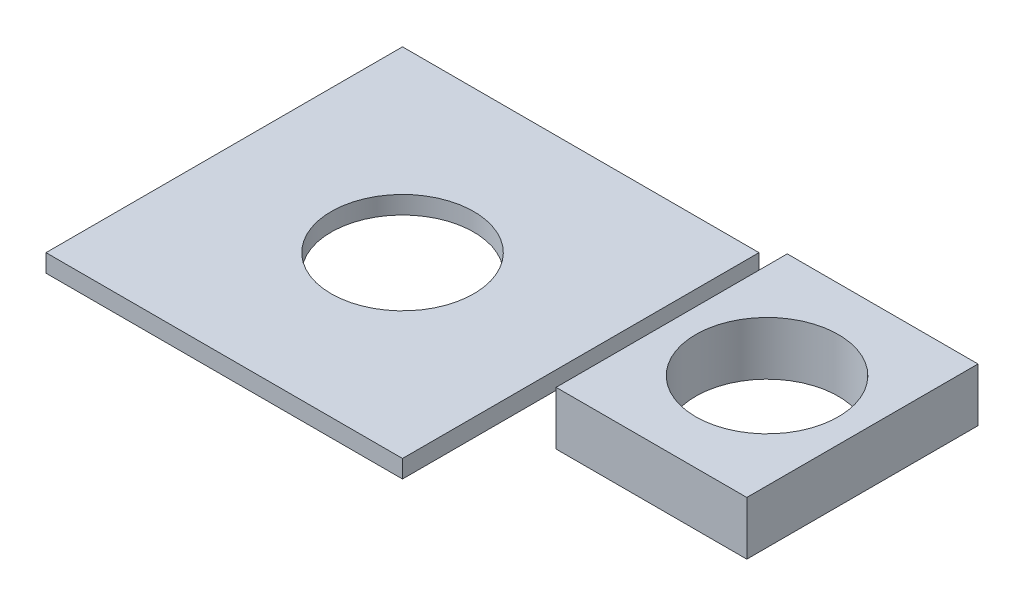
SolidWorks part; units mm, degrees
ref_plane "Front Plane" through (0, 0, 0) normal (0, 0, 1) x (1, 0, 0)
ref_plane "Top Plane" through (0, 0, 0) normal (0, 1, 0) x (1, 0, 0)
ref_plane "Right Plane" through (0, 0, 0) normal (1, 0, 0) x (0, 0, -1)
sketch "Sketch1" plane through (0, 0, 0) normal (0, 1, 0) x (1, 0, 0)
  line L1 (-5.35, -6.485) -> (5.35, -6.485)
  line L2 (-5.35, -6.485) -> (-5.35, 6.485)
  line L3 (-5.35, 6.485) -> (5.35, 6.485)
  line L4 (5.35, -6.485) -> (5.35, 6.485)
  line L5 (-5.35, -6.485) -> (5.35, 6.485) construction
  line L6 (-5.35, 6.485) -> (5.35, -6.485) construction
  circle A0 centre (0, 0) radius 4
  point P0 (0, 0)
  dimension "D3" = 8
  dimension "D1" = 12.97
  dimension "D2" = 10.7
extrude "Boss-Extrude1" add sketch "Sketch1" along normal blind 3
sketch "Sketch2" plane through (0, 0, 0) normal (0, 1, 0) x (1, 0, 0)
  line L1 (-28.2017, 7.7507) -> (-8.2017, 7.7507)
  line L2 (-28.2017, 7.7507) -> (-28.2017, -12.2493)
  line L3 (-28.2017, -12.2493) -> (-8.2017, -12.2493)
  line L4 (-8.2017, 7.7507) -> (-8.2017, -12.2493)
  line L5 (-28.2017, 7.7507) -> (-8.2017, -12.2493) construction
  line L6 (-28.2017, -12.2493) -> (-8.2017, 7.7507) construction
  circle A0 centre (-18.2017, -2.2493) radius 4
  point P0 (-18.2017, -2.2493)
  dimension "D3" = 8
  dimension "D1" = 20
  dimension "D2" = 20
extrude "Boss-Extrude2" add sketch "Sketch2" along normal blind 1
